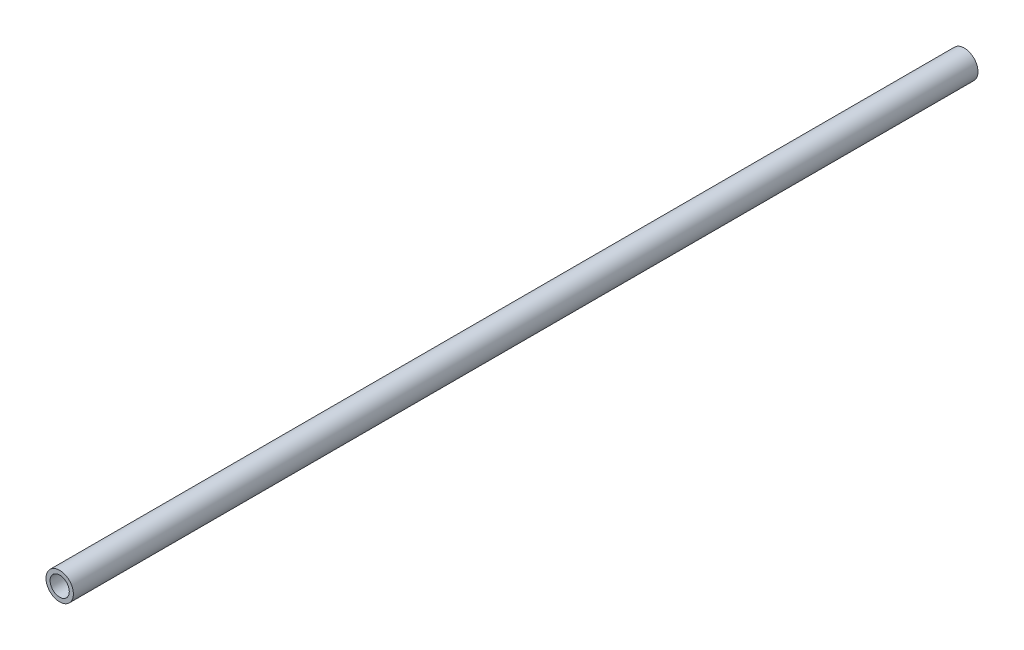
SolidWorks part; units mm, degrees
material "6061 合金"
ref_plane "前视基准面" through (0, 0, 0) normal (0, 0, 1) x (1, 0, 0)
ref_plane "上视基准面" through (0, 0, 0) normal (0, 1, 0) x (1, 0, 0)
ref_plane "右视基准面" through (0, 0, 0) normal (1, 0, 0) x (0, 0, -1)
sketch "草图1" plane through (0, 0, 0) normal (0, 0, 1) x (1, 0, 0)
  circle A0 centre (0, 0) radius 5
  circle A1 centre (0, 0) radius 3.5
  dimension "D1" = 10
  dimension "D2" = 1.5
extrude "凸台-拉伸1" add sketch "草图1" along normal mid plane 330
